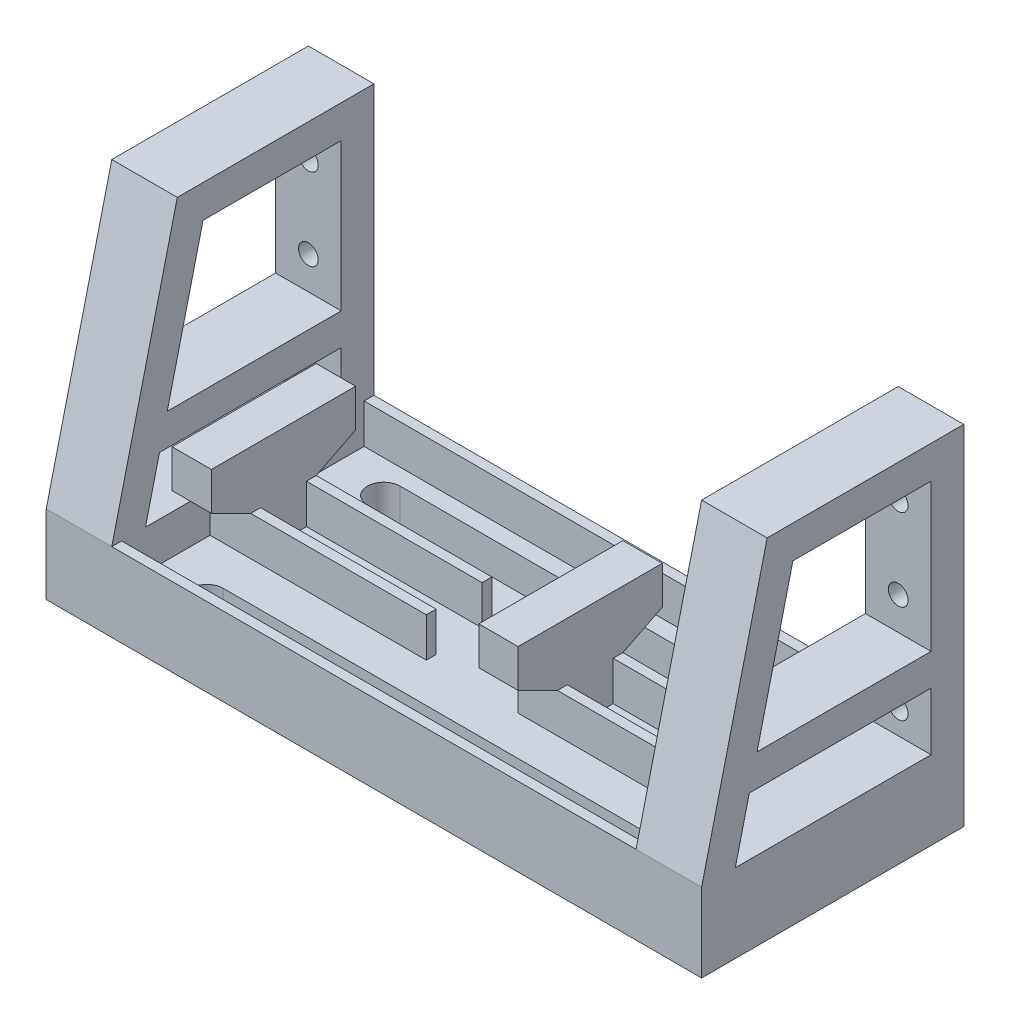
SolidWorks part; units mm, degrees
ref_plane "Front Plane" through (0, 0, 0) normal (0, 0, 1) x (1, 0, 0)
ref_plane "Top Plane" through (0, 0, 0) normal (0, 1, 0) x (1, 0, 0)
ref_plane "Right Plane" through (0, 0, 0) normal (1, 0, 0) x (0, 0, -1)
sketch "Sketch1" plane through (0, 0, 0) normal (1, 0, 0) x (0, 0, -1)
  line L16 (0, 0) -> (40, 0)
  line L17 (40, 0) -> (40, 12)
  line L18 (40, 12) -> (38.5, 12)
  line L19 (38.5, 12) -> (38.5, 6)
  line L20 (38.5, 6) -> (25, 6)
  line L21 (25, 6) -> (25, 12)
  line L22 (25, 12) -> (23.5, 12)
  line L23 (23.5, 12) -> (23.5, 6)
  line L24 (23.5, 6) -> (16.5, 6)
  line L25 (16.5, 6) -> (16.5, 12)
  line L26 (16.5, 12) -> (15, 12)
  line L27 (15, 12) -> (15, 6)
  line L28 (15, 6) -> (1.5, 6)
  line L29 (1.5, 6) -> (1.5, 12)
  line L30 (1.5, 12) -> (0, 12)
  line L31 (0, 12) -> (0, 0)
  dimension "D1" = 40
  dimension "D2" = 1.5
  dimension "D3" = 10
  dimension "D4" = 6
  dimension "D5" = 12
extrude "Boss-Extrude1" add sketch "Sketch1" along normal blind 80
ref_plane "Plane3" through (40, 0, 0) normal (1, 0, 0) x (0, 0, -1)
ref_plane "Plane1" through (6.2, 0, 0) normal (1, 0, 0) x (0, 0, -1)
sketch "Sketch2" plane through (6.2, 0, 0) normal (1, 0, 0) x (0, 0, -1)
  line L0 (15, 6) -> (15, 12)
  line L1 (15, 12) -> (9, 15)
  line L2 (9, 15) -> (9, 20.8)
  line L3 (9, 20.8) -> (31, 20.8)
  line L4 (31, 20.8) -> (31, 15)
  line L5 (31, 15) -> (25, 12)
  line L6 (25, 12) -> (25, 6)
  line L7 (25, 6) -> (15, 6)
  line L8 (23.5, 6) -> (16.5, 6) construction
  line L9 (15, 12) -> (15, 6) construction
  point P0 (20, 6)
  point P9 (20, 6)
  point P22 (20, 20.8)
  dimension "D1" = 14.8
  dimension "D2" = 3
  dimension "D3" = 22
  dimension "D4" = 6
extrude "Boss-Extrude2" add sketch "Sketch2" against normal blind 6
ref_plane "Plane2" through (47, 0, 0) normal (1, 0, 0) x (0, 0, -1)
sketch "Sketch4" plane through (47, 0, 0) normal (1, 0, 0) x (0, 0, -1)
  line L0 (25, 6) -> (15, 6) construction
  line L1 (15, 6) -> (15, 12) construction
  line L2 (25, 12) -> (25, 6) construction
  line L3 (31, 20.8) -> (31, 15) construction
  line L4 (31, 15) -> (25, 12) construction
  line L5 (15, 12) -> (9, 15) construction
  line L6 (9, 15) -> (9, 20.8) construction
  line L7 (9, 20.8) -> (31, 20.8) construction
  line L8 (25, 6) -> (15, 6)
  line L9 (15, 6) -> (15, 12)
  line L10 (25, 12) -> (25, 6)
  line L11 (31, 20.8) -> (31, 15)
  line L12 (31, 15) -> (25, 12)
  line L13 (15, 12) -> (9, 15)
  line L14 (9, 15) -> (9, 20.8)
  line L15 (9, 20.8) -> (31, 20.8)
extrude "Boss-Extrude3" add sketch "Sketch4" along normal blind 6
sketch "Sketch5" plane through (0, 0, 0) normal (0, -1, 0) x (1, 0, 0)
  line L0 (8, -31) -> (72, -31)
  line L1 (72, -36) -> (8, -36)
  line L2 (40, -40) -> (40, 0) construction
  line L3 (80, -40) -> (0, -40) construction
  line L4 (80, 0) -> (0, 0) construction
  line L5 (0, -20) -> (80, -20) construction
  line L6 (0, -23.5) -> (0, -16.5) construction
  line L7 (80, -23.5) -> (80, -16.5) construction
  line L8 (72, -4) -> (8, -4)
  line L9 (8, -9) -> (72, -9)
  line L10 (80, -38.5) -> (80, -25) construction
  arc A0 (72, -31) -> (72, -36) centre (72, -33.5) cw
  arc A1 (8, -36) -> (8, -31) centre (8, -33.5) cw
  arc A2 (8, -4) -> (8, -9) centre (8, -6.5) ccw
  arc A3 (72, -9) -> (72, -4) centre (72, -6.5) ccw
  point P18 (40, -36)
  point P29 (40, -4)
  dimension "D1" = 8
  dimension "D2" = 4
  dimension "D3" = 5
extrude "Cut-Extrude1" cut sketch "Sketch5" against normal up to next
sketch "Sketch6" plane through (0, 6, 0) normal (0, 1, 0) x (1, 0, 0)
  line L0 (47, 15) -> (6.2, 15) construction
  line L1 (47, 25) -> (33, 25)
  line L2 (47, 25) -> (47, 15)
  line L3 (47, 15) -> (33, 15)
  line L4 (33, 25) -> (33, 15)
  line L5 (80, 25) -> (0, 25) construction
  line L6 (40, -2.1179) -> (40, 2.1179) construction
  point P7 (40, 15)
  dimension "D1" = 14
extrude "Cut-Extrude2" cut sketch "Sketch6" along normal up to next
sketch "Sketch7" plane through (80, 0, 0) normal (1, 0, 0) x (0, 0, -1)
  line L0 (0, 0) -> (40, 0)
  line L1 (40, 0) -> (40, 12)
  line L2 (40, 12) -> (40, 53.1587)
  line L3 (40, 53.1587) -> (10, 53.1587)
  line L4 (10, 53.1587) -> (0, 12)
  line L5 (0, 12) -> (0, 0)
  line L6 (35, 48.1587) -> (13.9306, 48.1587)
  line L7 (13.9306, 48.1587) -> (8.464, 25.6587)
  line L8 (8.464, 25.6587) -> (35, 25.6587)
  line L9 (35, 25.6587) -> (35, 48.1587)
  line L10 (35, 20.8) -> (7.2835, 20.8)
  line L11 (7.2835, 20.8) -> (5.1455, 12)
  line L12 (5.1455, 12) -> (35, 12)
  line L13 (35, 12) -> (35, 20.8)
  line L14 (8.464, 25.6587) -> (7.2835, 20.8) construction
  line L15 (13.9306, 48.1587) -> (13.9306, 53.1587) construction
  line L16 (8.464, 25.6587) -> (3.6053, 26.8391) construction
  line L17 (35, 48.1587) -> (40, 48.1587) construction
  line L18 (25, 12) -> (23.5, 12) construction
  line L19 (31, 20.8) -> (9, 20.8) construction
  point P4 (20, 0)
  dimension "D1" = 5
  dimension "D2" = 10
  dimension "D3" = 22.5
extrude "Boss-Extrude4" add sketch "Sketch7" along normal blind 10
sketch "Sketch8" plane through (0, 0, 0) normal (-1, 0, 0) x (0, 0, 1)
  line L28 (0, 12) -> (0, 0) construction
  line L29 (0, 0) -> (-40, 0) construction
  line L30 (-40, 0) -> (-40, 12) construction
  line L31 (-5.1455, 12) -> (-35, 12) construction
  line L32 (-7.2835, 20.8) -> (-5.1455, 12) construction
  line L33 (-35, 12) -> (-35, 20.8) construction
  line L34 (-35, 20.8) -> (-7.2835, 20.8) construction
  line L35 (-13.9306, 48.1587) -> (-8.464, 25.6587) construction
  line L36 (-8.464, 25.6587) -> (-35, 25.6587) construction
  line L37 (-35, 25.6587) -> (-35, 48.1587) construction
  line L38 (-35, 48.1587) -> (-13.9306, 48.1587) construction
  line L39 (-10, 53.1587) -> (0, 12) construction
  line L40 (-40, 53.1587) -> (-10, 53.1587) construction
  line L41 (-40, 12) -> (-40, 53.1587) construction
  line L42 (0, 12) -> (0, 0)
  line L43 (0, 0) -> (-40, 0)
  line L44 (-40, 0) -> (-40, 12)
  line L45 (-5.1455, 12) -> (-35, 12)
  line L46 (-7.2835, 20.8) -> (-5.1455, 12)
  line L47 (-35, 12) -> (-35, 20.8)
  line L48 (-35, 20.8) -> (-7.2835, 20.8)
  line L49 (-13.9306, 48.1587) -> (-8.464, 25.6587)
  line L50 (-8.464, 25.6587) -> (-35, 25.6587)
  line L51 (-35, 25.6587) -> (-35, 48.1587)
  line L52 (-35, 48.1587) -> (-13.9306, 48.1587)
  line L53 (-10, 53.1587) -> (0, 12)
  line L54 (-40, 53.1587) -> (-10, 53.1587)
  line L55 (-40, 12) -> (-40, 53.1587)
extrude "Boss-Extrude11" add sketch "Sketch8" along normal blind 10
sketch "Sketch9" plane through (0, 0, -40) normal (0, 0, -1) x (-1, 0, 0)
  line L0 (-90, 53.1587) -> (-80, 53.1587) construction
  line L1 (10, 53.1587) -> (0, 53.1587) construction
  circle A0 centre (-85, 43.1587) radius 1.5
  circle A1 centre (-85, 30.6587) radius 1.5
  circle A2 centre (-85, 15.6587) radius 1.5
  circle A3 centre (5, 43.1587) radius 1.5
  circle A4 centre (5, 30.6587) radius 1.5
  circle A5 centre (5, 15.6587) radius 1.5
  point P6 (-85, 53.1587)
  point P9 (-85, 53.1587)
  point P12 (5, 53.1587)
  dimension "D1" = 3
  dimension "D2" = 10
  dimension "D3" = 12.5
  dimension "D4" = 37.5
  dimension "D5" = 2
extrude "Cut-Extrude3" cut sketch "Sketch9" against normal up to next
